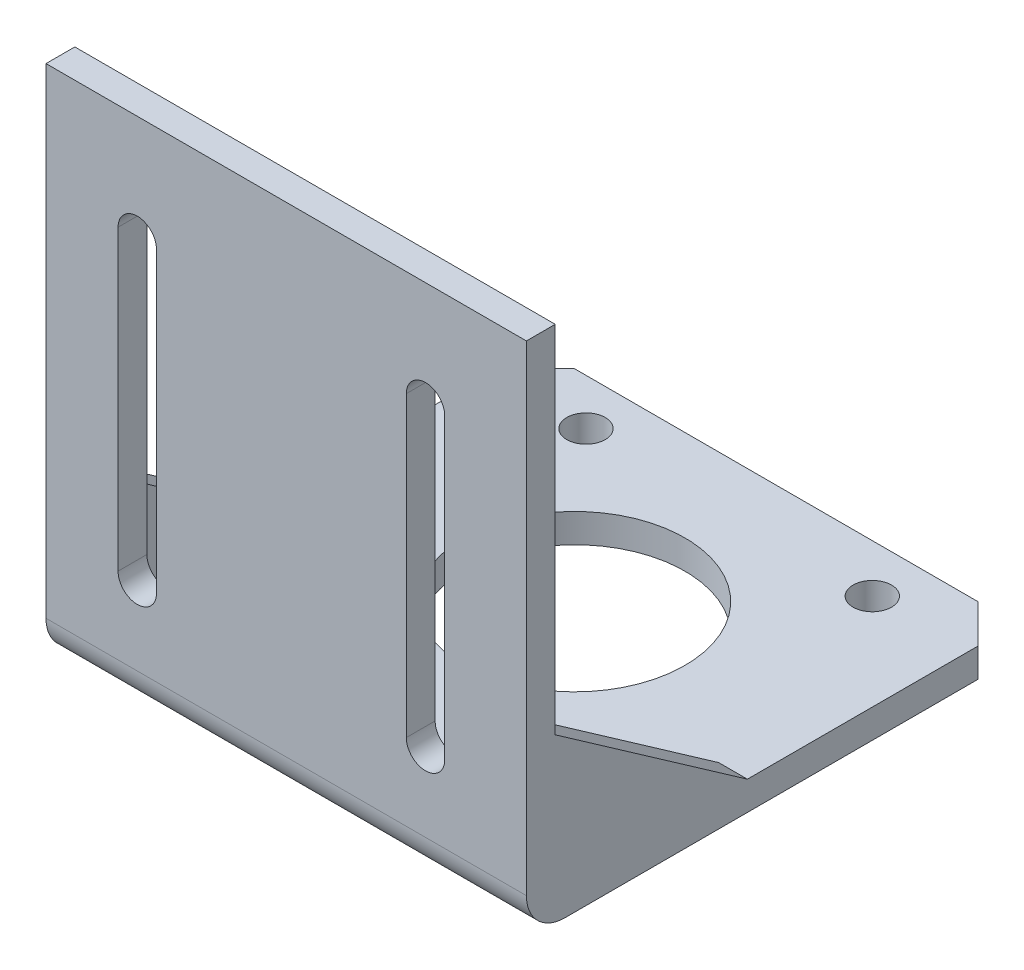
SolidWorks part; units mm, degrees
ref_plane "Front Plane" through (0, 0, 0) normal (0, 0, 1) x (1, 0, 0)
ref_plane "Top Plane" through (0, 0, 0) normal (0, 1, 0) x (1, 0, 0)
ref_plane "Right Plane" through (0, 0, 0) normal (1, 0, 0) x (0, 0, -1)
sketch "Sketch1" plane through (0, 0, 0) normal (0, 1, 0) x (1, 0, 0)
  line L0 (21, 23.7976) -> (25, 19.7976)
  line L1 (-21, 23.7976) -> (21, 23.7976)
  line L2 (-25, 19.7976) -> (-25, -24.2024)
  line L3 (-25, -24.2024) -> (25, -24.2024)
  line L4 (25, 19.7976) -> (25, -24.2024)
  line L5 (-25, 23.7976) -> (25, -24.2024) construction
  line L6 (-25, -24.2024) -> (25, 23.7976) construction
  line L7 (-25, 19.7976) -> (-21, 23.7976)
  circle A0 centre (0, 2.7976) radius 11.5
  circle A1 centre (-15, 19) radius 2
  circle A2 centre (15, 18.7976) radius 2
  circle A3 centre (15, -12.2024) radius 2
  circle A4 centre (-15, -12.2024) radius 2
  point P0 (0, 0)
  point P20 (-12.3016, 20)
  point P21 (-21, -6.25)
  point P22 (-15, -7.4405)
  point P23 (15, -12.2024)
  point P24 (-15, -12.2024)
  dimension "D3" = 23
  dimension "D4" = 21
  dimension "D6" = 4
  dimension "D9" = 4
  dimension "D10" = 4
  dimension "D11" = 4
  dimension "D1" = 50
  dimension "D2" = 48
  dimension "D5" = 10
  dimension "D12" = 5
  dimension "D13" = 10
  dimension "D14" = 31
extrude "Boss-Extrude1" add sketch "Sketch1" along normal blind 3
sketch "Sketch2" plane through (0, 0, 24.2024) normal (0, 0, 1) x (1, 0, 0)
  line L0 (-25, 0) -> (-25, 54)
  line L1 (-25, 54) -> (25, 54)
  line L2 (25, 54) -> (25, 0)
  line L3 (25, 0) -> (-25, 0)
  line L4 (-17.5, 43) -> (-17.5, 12)
  line L5 (-13.5, 43) -> (-13.5, 12)
  line L6 (12.5, 43) -> (12.5, 12)
  line L7 (16.5, 43) -> (16.5, 12)
  line L8 (-15.5, 45) -> (14.5, 45) construction
  line L9 (14.5, 10) -> (-15.5, 10) construction
  arc A0 (-17.5, 12) -> (-13.5, 12) centre (-15.5, 12) ccw
  arc A1 (-17.5, 43) -> (-13.5, 43) centre (-15.5, 43) cw
  arc A2 (12.5, 43) -> (16.5, 43) centre (14.5, 43) cw
  arc A3 (12.5, 12) -> (16.5, 12) centre (14.5, 12) ccw
  dimension "D6" = 35
  dimension "D1" = 54
  dimension "D2" = 4
  dimension "D3" = 7.5
  dimension "D4" = 4
  dimension "D5" = 26
  dimension "D7" = 11
extrude "Boss-Extrude2" add sketch "Sketch2" along normal blind 3
fillet "Fillet1" radius 4 1 edges at (0, 0, 27.2024)
fillet "Fillet2" radius 2 1 edges at (0, 3, 24.2024)
sketch "Sketch6" plane through (25, 0, 0) normal (1, 0, 0) x (0, 0, -1)
  line L0 (-24.2024, 3) -> (-24.2024, 17)
  line L1 (-24.2024, 5) -> (-24.2024, 54) construction
  line L2 (-24.2024, 17) -> (-4.2024, 3)
  line L3 (-22.2024, 3) -> (19.7976, 3) construction
  line L4 (-4.2024, 3) -> (-24.2024, 3)
  dimension "D1" = 20
  dimension "D2" = 14
extrude "Boss-Extrude3" add sketch "Sketch6" against normal blind 3
mirror "Mirror1" about plane through (0, 0, 0) normal (1, 0, 0) of "Boss-Extrude3"
